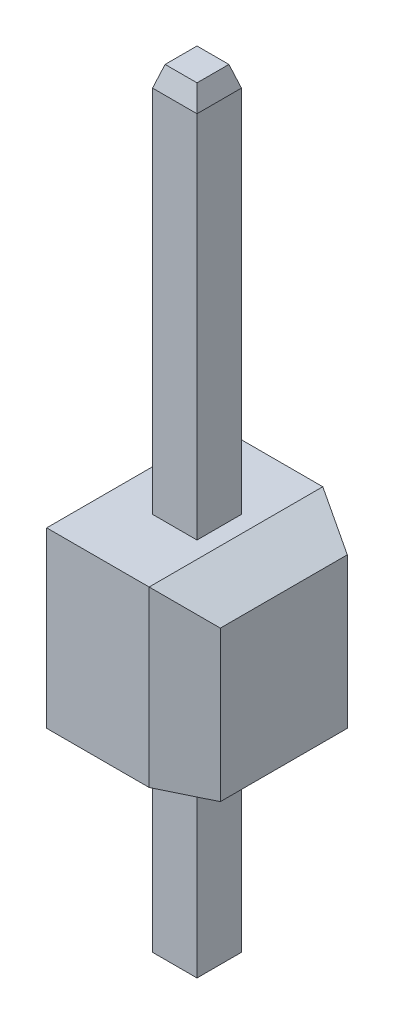
SolidWorks part; units mm, degrees
ref_plane "Front Plane" through (0, 0, 0) normal (0, 0, 1) x (1, 0, 0)
ref_plane "Top Plane" through (0, 0, 0) normal (0, 1, 0) x (1, 0, 0)
ref_plane "Right Plane" through (0, 0, 0) normal (1, 0, 0) x (0, 0, -1)
ref_plane "Plane1" through (1.27, 0, 0) normal (1, 0, 0) x (0, 0, -1)
sketch "Sketch1" plane through (1.27, 0, 0) normal (1, 0, 0) x (0, 0, -1)
  line L0 (-1.27, 0) -> (1.27, 0)
  line L1 (1.27, 0) -> (1.27, 2.54)
  line L2 (1.27, 2.54) -> (-1.27, 2.54)
  line L3 (-1.27, 2.54) -> (-1.27, 0)
extrude "Boss-Extrude1" add sketch "Sketch1" against normal blind 2.54
sketch "Sketch2" plane through (0, 2.54, 0) normal (0, 1, 0) x (-1, 0, 0)
  line L0 (-0.325, 0.325) -> (0.325, 0.325)
  line L1 (0.325, 0.325) -> (0.325, -0.325)
  line L2 (0.325, -0.325) -> (-0.325, -0.325)
  line L3 (-0.325, -0.325) -> (-0.325, 0.325)
extrude "Boss-Extrude2" add sketch "Sketch2" along normal blind 5.7
sketch "Sketch3" plane through (0, 0, 0) normal (0, -1, 0) x (1, 0, 0)
  line L0 (-0.325, -0.325) -> (-0.325, 0.325)
  line L1 (-0.325, 0.325) -> (0.325, 0.325)
  line L2 (0.325, 0.325) -> (0.325, -0.325)
  line L3 (0.325, -0.325) -> (-0.325, -0.325)
extrude "Boss-Extrude3" add sketch "Sketch3" along normal blind 3.1
chamfer "Chamfer1" distance 0.0917 angle 73 4 edges at (-0.325, 8.24, 0) (0, 8.24, 0.325) (0, 8.24, -0.325) (0.325, 8.24, 0)
chamfer "Chamfer2" distance 0.3 angle 17 4 edges at (0, -3.1, 0.325) (-0.325, -3.1, 0) (0.325, -3.1, 0) (0, -3.1, -0.325)
chamfer "Chamfer3" distance 0.7 angle 26 6 edges at (1.27, 1.27, 1.27) (1.27, 1.27, -1.27) (1.27, 2.54, 0) (-1.27, 1.27, 1.27) (-1.27, 2.54, 0) (-1.27, 1.27, -1.27)
